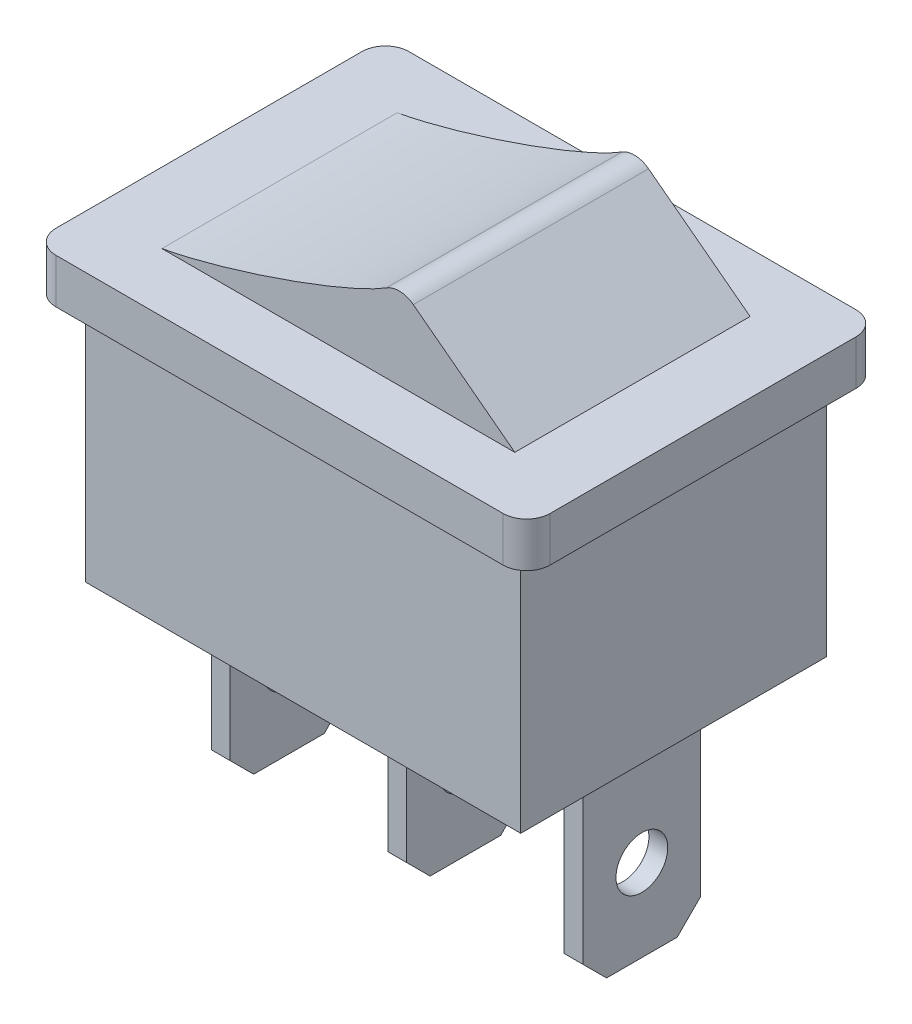
SolidWorks part; units mm, degrees
ref_plane "Front Plane" through (0, 0, 0) normal (0, 0, 1) x (1, 0, 0)
ref_plane "Top Plane" through (0, 0, 0) normal (0, 1, 0) x (1, 0, 0)
ref_plane "Right Plane" through (0, 0, 0) normal (1, 0, 0) x (0, 0, -1)
sketch "Sketch1" plane through (0, 0, 0) normal (0, 1, 0) x (1, 0, 0)
  line L1 (-10.5, -7.5) -> (10.5, -7.5)
  line L2 (-10.5, -7.5) -> (-10.5, 7.5)
  line L3 (-10.5, 7.5) -> (10.5, 7.5)
  line L4 (10.5, -7.5) -> (10.5, 7.5)
  line L5 (-10.5, -7.5) -> (10.5, 7.5) construction
  line L6 (-10.5, 7.5) -> (10.5, -7.5) construction
  point P0 (0, 0)
  dimension "D1" = 21
  dimension "D2" = 15
extrude "Boss-Extrude1" add sketch "Sketch1" along normal blind 1.9
fillet "Fillet1" radius 1 4 edges at (-10.5, 0.95, -7.5) (10.5, 0.95, 7.5) (10.5, 0.95, -7.5) (-10.5, 0.95, 7.5)
sketch "Sketch2" plane through (0, 0, 0) normal (0, -1, 0) x (1, 0, 0)
  line L1 (-9.25, -6.5) -> (9.25, -6.5)
  line L2 (-9.25, -6.5) -> (-9.25, 6.5)
  line L3 (-9.25, 6.5) -> (9.25, 6.5)
  line L4 (9.25, -6.5) -> (9.25, 6.5)
  line L5 (-9.25, -6.5) -> (9.25, 6.5) construction
  line L6 (-9.25, 6.5) -> (9.25, -6.5) construction
  point P0 (0, 0)
  dimension "D1" = 13
  dimension "D2" = 18.5
extrude "Boss-Extrude2" add sketch "Sketch2" along normal blind 10.5
sketch "Sketch4" plane through (0, 0, -6.5) normal (0, 0, -1) x (-1, 0, 0)
  line L1 (-9.5, 1.9) -> (9.5, 1.9) construction
  line L3 (7.5, 1.9) -> (-7.5, 1.9)
  line L4 (-7.5, 1.9) -> (-2.5, 5.7)
  line L5 (0, 1.9) -> (0, 0) construction
  ellipse E0 centre (3.2165, 3.8) end of major axis (-2.5, 5.7) minor radius 0.7142
  dimension "D1" = 5
  dimension "D2" = 15
  dimension "D3" = 3.8
extrude "Boss-Extrude3" add sketch "Sketch4" along normal mid plane 10 from surface at -6.5 contours E0 L4 L3 starting at plane "Front Plane"
fillet "Fillet2" radius 1 1 edges at (2.5, 5.7, 0)
sketch "Sketch5" plane through (0, -10.5, 0) normal (0, -1, 0) x (1, 0, 0)
  line L0 (7.1, -2.5) -> (7.1, 2.5)
  line L1 (-0.4, -2.5) -> (0.4, -2.5)
  line L2 (-0.4, -2.5) -> (-0.4, 2.5)
  line L3 (-0.4, 2.5) -> (0.4, 2.5)
  line L4 (0.4, -2.5) -> (0.4, 2.5)
  line L5 (-0.4, -2.5) -> (0.4, 2.5) construction
  line L6 (-0.4, 2.5) -> (0.4, -2.5) construction
  line L7 (7.1, -2.5) -> (7.9, -2.5)
  line L8 (7.9, -2.5) -> (7.9, 2.5)
  line L9 (7.1, 2.5) -> (7.9, 2.5)
  line L10 (-7.9, -2.5) -> (-7.1, -2.5)
  line L11 (-7.9, -2.5) -> (-7.9, 2.5)
  line L12 (-7.9, 2.5) -> (-7.1, 2.5)
  line L13 (-7.1, -2.5) -> (-7.1, 2.5)
  line L14 (-7.9, -2.5) -> (-7.1, 2.5) construction
  line L15 (-7.9, 2.5) -> (-7.1, -2.5) construction
  point P0 (0, 0)
  point P12 (-7.5, 0)
  dimension "D1" = 0.8
  dimension "D2" = 5
  dimension "D5" = 6.7
  dimension "D6" = 6.7
  dimension "D3" = 2
  dimension "D4" = 2
extrude "Boss-Extrude4" add sketch "Sketch5" along normal blind 8.5
chamfer "Chamfer1" distance 1 angle 45 6 edges at (7.5, -19, -2.5) (-7.5, -19, -2.5) (0, -19, -2.5) (7.5, -19, 2.5) (0, -19, 2.5) (-7.5, -19, 2.5)
sketch "Sketch6" plane through (-7.9, 0, 0) normal (-1, 0, 0) x (0, 0, 1)
  line L0 (0.1306, 0.8892) -> (0, -15.5) construction
  line L1 (1.5, -19) -> (-1.5, -19) construction
  circle A0 centre (0, -15.5) radius 1.1
  dimension "D1" = 2.2
  dimension "D2" = 3.5
extrude "Cut-Extrude1" cut sketch "Sketch6" against normal through all
